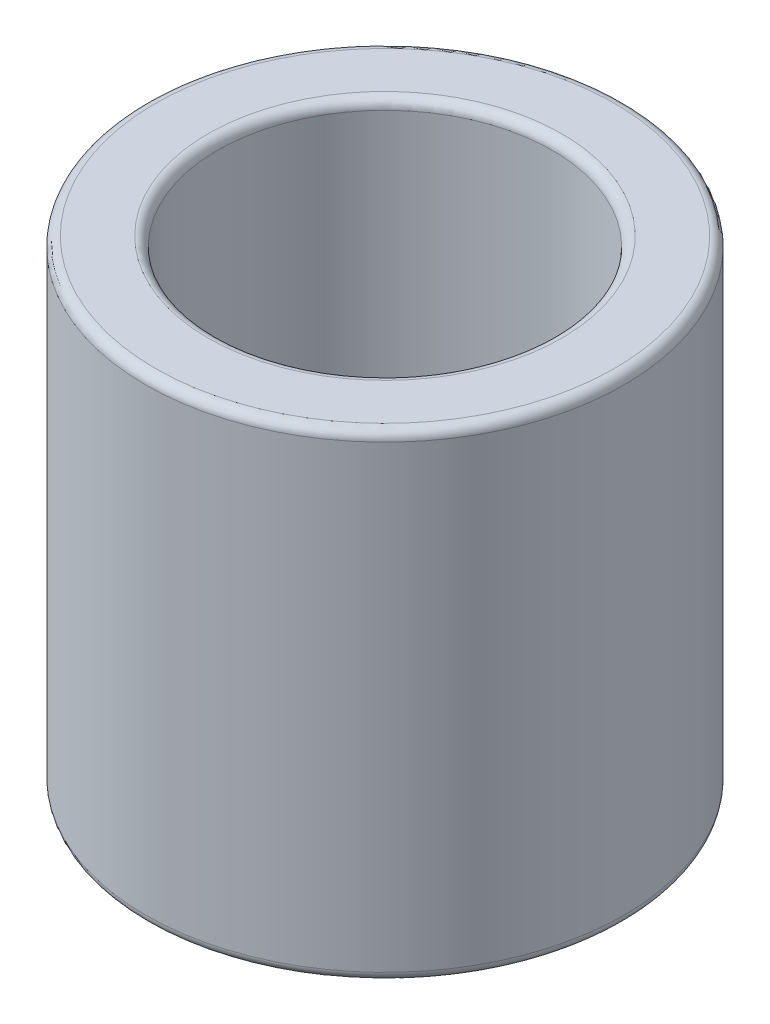
SolidWorks part; units mm, degrees
ref_plane "Front Plane" through (0, 0, 0) normal (0, 0, 1) x (1, 0, 0)
ref_plane "Top Plane" through (0, 0, 0) normal (0, 1, 0) x (1, 0, 0)
ref_plane "Right Plane" through (0, 0, 0) normal (1, 0, 0) x (0, 0, -1)
sketch "Sketch1" plane through (0, 0, 0) normal (0, 1, 0) x (1, 0, 0)
  circle A0 centre (0, 0) radius 1.75
  circle A1 centre (0, 0) radius 2.5
  dimension "D1" = 3.5
  dimension "D2" = 5
extrude "Boss-Extrude1" add sketch "Sketch1" along normal blind 5
fillet "Fillet1" radius 0.1 4 edges at (0, 0, 1.75) (0, 0, 2.5) (0, 5, 1.75) (0, 5, 2.5)
